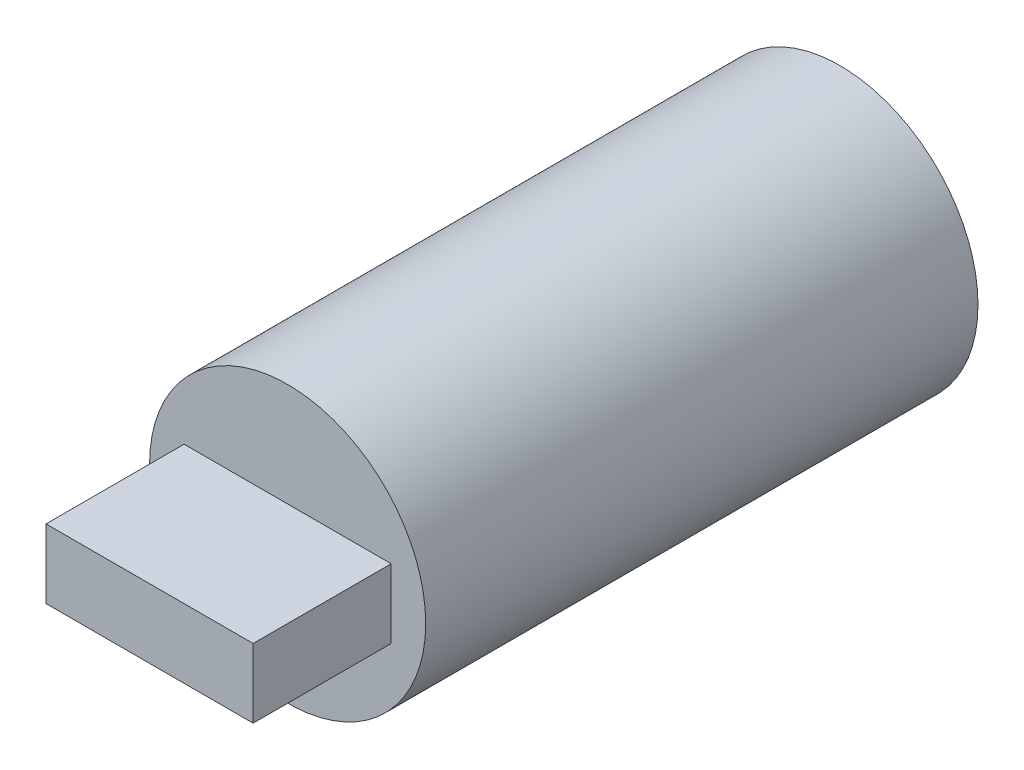
SolidWorks part; units mm, degrees
material "1.7036 (28CrS4)"
ref_plane "정면" through (0, 0, 0) normal (0, 0, 1) x (1, 0, 0)
ref_plane "윗면" through (0, 0, 0) normal (0, 1, 0) x (1, 0, 0)
ref_plane "우측면" through (0, 0, 0) normal (1, 0, 0) x (0, 0, -1)
sketch "스케치1" plane through (0, 0, 0) normal (0, 0, 1) x (1, 0, 0)
  circle A0 centre (0, 0) radius 10
  dimension "D1" = 20
extrude "보스-돌출1" add sketch "스케치1" along normal blind 40
sketch "스케치2" plane through (0, 0, 40) normal (0, 0, 1) x (1, 0, 0)
  line L1 (-7.5, 2.5) -> (7.5, 2.5)
  line L2 (-7.5, 2.5) -> (-7.5, -2.5)
  line L3 (-7.5, -2.5) -> (7.5, -2.5)
  line L4 (7.5, 2.5) -> (7.5, -2.5)
  line L5 (-7.5, 2.5) -> (7.5, -2.5) construction
  line L6 (-7.5, -2.5) -> (7.5, 2.5) construction
  point P0 (0, 0)
  dimension "D1" = 15
  dimension "D2" = 5
extrude "보스-돌출2" add sketch "스케치2" along normal blind 10
